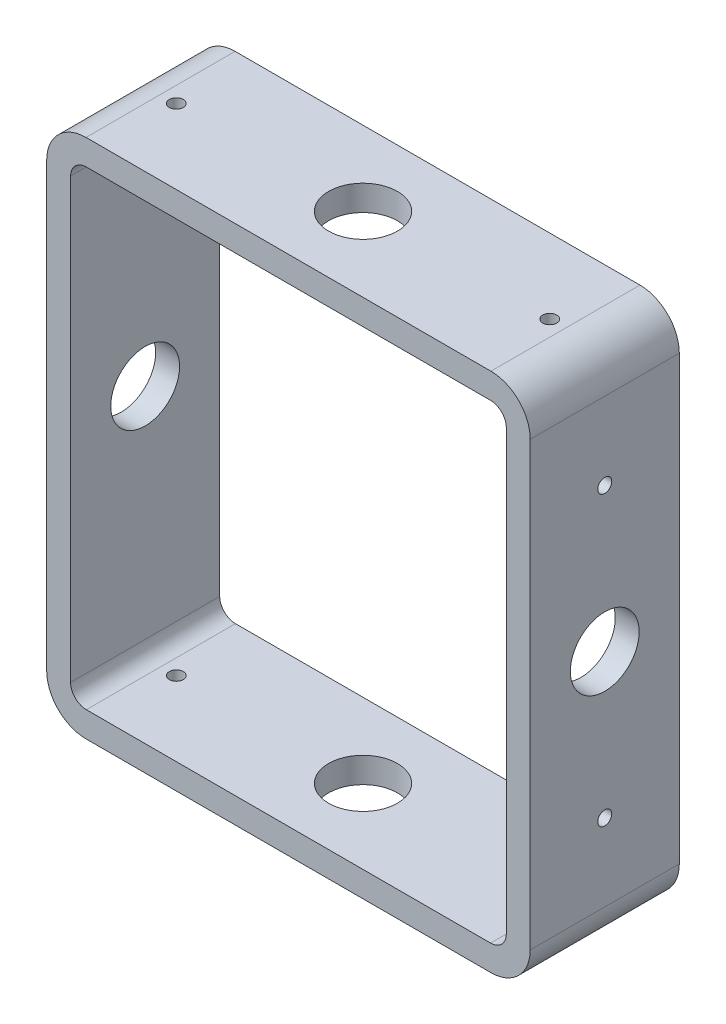
SolidWorks part; units mm, degrees
ref_plane "Front Plane" through (0, 0, 0) normal (0, 0, 1) x (1, 0, 0)
ref_plane "Top Plane" through (0, 0, 0) normal (0, 1, 0) x (1, 0, 0)
ref_plane "Right Plane" through (0, 0, 0) normal (1, 0, 0) x (0, 0, -1)
sketch "Sketch2" plane through (0, 0, 0) normal (0, 0, 1) x (1, 0, 0)
  line L1 (-39.0271, -42.0433) -> (39.0271, -42.0433)
  line L2 (-39.0271, -42.0433) -> (-39.0271, 42.0433)
  line L3 (-39.0271, 42.0433) -> (39.0271, 42.0433)
  line L4 (39.0271, -42.0433) -> (39.0271, 42.0433)
  line L5 (-39.0271, -42.0433) -> (39.0271, 42.0433) construction
  line L6 (-39.0271, 42.0433) -> (39.0271, -42.0433) construction
  line L7 (-35.1663, -37.9349) -> (35.1663, -37.9349)
  line L8 (-35.1663, -37.9349) -> (-35.1663, 37.9349)
  line L9 (-35.1663, 37.9349) -> (35.1663, 37.9349)
  line L10 (35.1663, -37.9349) -> (35.1663, 37.9349)
  line L11 (-35.1663, -37.9349) -> (35.1663, 37.9349) construction
  line L12 (-35.1663, 37.9349) -> (35.1663, -37.9349) construction
  point P0 (0, 0)
  point P6 (0, 0)
  dimension "D1" = 78.0542
  dimension "D2" = 84.0867
  dimension "D3" = 70.3326
  dimension "D4" = 75.8698
extrude "Boss-Extrude1" add sketch "Sketch2" along normal blind 24.0665
sketch "Sketch4" plane through (-39.0271, 0, 0) normal (-1, 0, 0) x (0, 0, 1)
  line L0 (24.0665, 42.0433) -> (0, 42.0433) construction
  line L1 (13.2366, 0) -> (-13.2366, 0) construction
  point P0 (12.0333, 0)
  point P3 (12.0333, 42.0433)
hole_wizard "7/16 (0.4375) Diameter Hole1" positions "Sketch5" profile "Sketch6" hole size "7/16" standard "ANSI Inch" end condition through all
sketch "Sketch5" plane through (-39.0271, 0, 0) normal (-1, 0, 0) x (0, 0, 1)
  point P0 (12.0333, 0)
sketch "Sketch6" plane through (-39.0271, 0, 12.0333) normal (0, 1, 0) x (0, 0, 1)
  line L0 (0, 0) -> (0, 78.0542)
  line L1 (0, 78.0542) -> (5.5562, 78.0542)
  line L2 (5.5562, 78.0542) -> (5.5562, 0)
  line L5 (5.5562, 0) -> (0, 0)
  line L11 (0, -6.35) -> (0, 107.95) construction
  dimension "Thru Hole Dia." = 11.1125
  dimension "Thru Hole Depth" = 78.0542
sketch "Sketch8" plane through (0, 42.0433, 0) normal (0, 1, 0) x (1, 0, 0)
  line L0 (39.0271, -24.0665) -> (39.0271, 0) construction
  line L1 (0, -13.2366) -> (0, 13.2366) construction
  point P0 (0, -12.0333)
  point P3 (39.0271, -12.0333)
hole_wizard "7/16 (0.4375) Diameter Hole2" positions "Sketch9" profile "Sketch10" hole size "7/16" standard "ANSI Inch" end condition through all
sketch "Sketch9" plane through (0, 42.0433, 0) normal (0, 1, 0) x (1, 0, 0)
  point P0 (0, -12.0333)
sketch "Sketch10" plane through (0, 42.0433, 12.0333) normal (1, 0, 0) x (0, 0, 1)
  line L0 (0, 0) -> (0, 84.0867)
  line L1 (0, 84.0867) -> (5.5562, 84.0867)
  line L2 (5.5562, 84.0867) -> (5.5562, 0)
  line L5 (5.5562, 0) -> (0, 0)
  line L11 (0, -6.35) -> (0, 107.95) construction
  dimension "Thru Hole Dia." = 11.1125
  dimension "Thru Hole Depth" = 84.0867
fillet "Fillet2" radius 6.35 4 edges at (39.0271, -42.0433, 12.0333) (-39.0271, -42.0433, 12.0333) (39.0271, 42.0433, 12.0333) (-39.0271, 42.0433, 12.0333)
fillet "Fillet3" radius 2.54 4 edges at (-35.1663, -37.9349, 12.0333) (-35.1663, 37.9349, 12.0333) (35.1663, -37.9349, 12.0333) (35.1663, 37.9349, 12.0333)
sketch "Sketch11" plane through (39.0271, 0, 0) normal (1, 0, 0) x (0, 0, -1)
  line L0 (-12.0333, 23.241) -> (-12.0333, -23.241) construction
  line L1 (13.2366, 0) -> (-13.2366, 0) construction
  point P0 (-12.0333, 23.241)
  point P1 (-12.0333, -23.241)
  point P7 (-12.0333, 0)
  dimension "D1" = 46.482
hole_wizard "#4-40 Tapped Hole1" positions "Sketch12" profile "Sketch13" tap size "#4-40" standard "ANSI Inch"
sketch "Sketch12" plane through (39.0271, 0, 0) normal (1, 0, 0) x (0, 0, -1)
  point P0 (-12.0333, 23.241)
  point P3 (-12.0333, -23.241)
sketch "Sketch13" plane through (39.0271, 23.241, 12.0333) normal (0, 1, 0) x (0, 0, -1)
  line L0 (0, 0) -> (0, 3.8608)
  line L1 (0, 3.8608) -> (1.1303, 3.8608)
  line L2 (1.1303, 3.8608) -> (1.1303, 0)
  line L5 (1.1303, 0) -> (0, 0)
  line L11 (0, -6.35) -> (0, 107.95) construction
  dimension "Thru Tap Drill Dia." = 2.2606
  dimension "Thru Tap Drill Depth" = 3.8608
cosmetic thread "Hole Thread1" parameters "D2"=2.8448
cosmetic thread "Hole Thread2" parameters "D2"=2.8448
sketch "Sketch14" plane through (0, -42.0433, 0) normal (0, -1, 0) x (1, 0, 0)
  line L0 (32.6771, 12.0333) -> (-32.6771, 12.0333) construction
  line L1 (32.6771, 0) -> (32.6771, 24.0665) construction
  line L2 (-32.6771, 24.0665) -> (-32.6771, 0) construction
  point P6 (30.1371, 12.0333)
  point P7 (-30.1371, 12.0332)
  dimension "D1" = 2.54
  dimension "D2" = 2.54
hole_wizard "#4-40 Tapped Hole2" positions "Sketch15" profile "Sketch17" tap size "#4-40" standard "ANSI Inch" end condition through all
sketch "Sketch15" plane through (0, -42.0433, 0) normal (0, -1, 0) x (-1, 0, 0)
  point P0 (-30.1371, -12.0333)
  point P3 (30.1371, -12.0332)
sketch "Sketch17" plane through (30.1371, -42.0433, 12.0333) normal (1, 0, 0) x (0, 0, -1)
  line L0 (0, 0) -> (0, 84.0867)
  line L1 (0, 84.0867) -> (1.1303, 84.0867)
  line L2 (1.1303, 84.0867) -> (1.1303, 0)
  line L5 (1.1303, 0) -> (0, 0)
  line L11 (0, -6.35) -> (0, 107.95) construction
  dimension "Thru Tap Drill Dia." = 2.2606
  dimension "Thru Tap Drill Depth" = 84.0867
cosmetic thread "Hole Thread3" parameters "D2"=2.8448
cosmetic thread "Hole Thread4" parameters "D2"=2.8448
